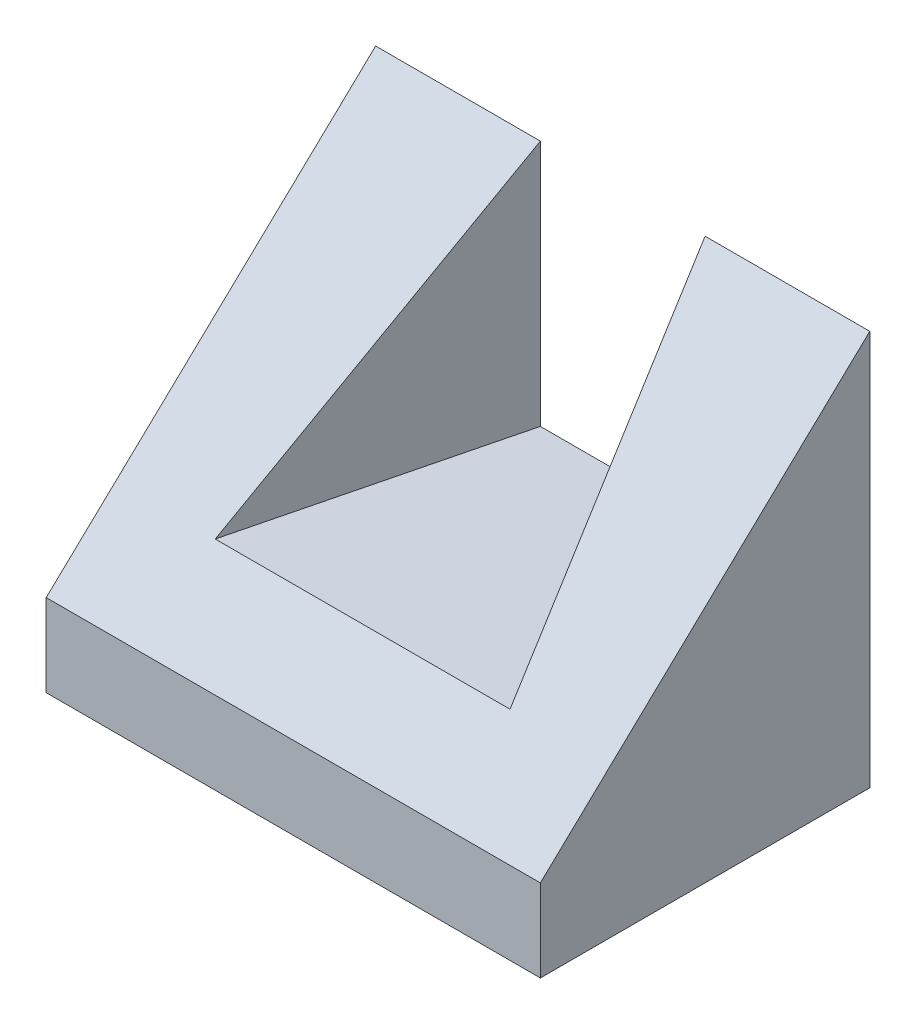
SolidWorks part; units mm, degrees
ref_plane "前基準面" through (0, 0, 0) normal (0, 0, 1) x (1, 0, 0)
ref_plane "上基準面" through (0, 0, 0) normal (0, 1, 0) x (1, 0, 0)
ref_plane "右基準面" through (0, 0, 0) normal (1, 0, 0) x (0, 0, -1)
sketch "草圖1" plane through (0, 0, 0) normal (0, 0, 1) x (1, 0, 0)
  line L1 (-15, 12) -> (15, 12)
  line L2 (-15, 12) -> (-15, -12)
  line L3 (-15, -12) -> (15, -12)
  line L4 (15, 12) -> (15, -12)
  line L5 (-15, 12) -> (15, -12) construction
  line L6 (-15, -12) -> (15, 12) construction
  point P0 (0, 0)
  dimension "D1" = 30
  dimension "D2" = 24
extrude "填料-伸長1" add sketch "草圖1" against normal blind 20
sketch "草圖2" plane through (0, 12, 0) normal (0, 1, 0) x (1, 0, 0)
  line L0 (5, 20) -> (10, 0)
  line L1 (15, 20) -> (-15, 20) construction
  line L2 (15, 0) -> (-15, 0) construction
  line L3 (10, 0) -> (-10, 0)
  line L4 (-10, 0) -> (-5, 20)
  line L5 (-5, 20) -> (5, 20)
  line L6 (5, 20) -> (5.0354, 19.9313)
  line L7 (0, 0) -> (0, 20) construction
  line M3 (-15, 0) -> (15, 0)
  line M5 (15, 20) -> (-15, 20)
  dimension "D1" = 10
  dimension "D2" = 20
extrude "除料-伸長1" cut sketch "草圖2" against normal blind 15 contours L7 L5 L4 M3 | L7 L3 L0 M5
sketch "草圖3" plane through (15, 0, 0) normal (1, 0, 0) x (0, 0, -1)
  line L0 (0, -7) -> (20, 12)
  line L1 (0, -12) -> (0, 12) construction
  line L2 (20, 12) -> (0, 12) construction
  line L3 (20, 12) -> (0, 12)
  line L4 (0, 12) -> (0, -7)
  line L5 (20, -12) -> (0, -12) construction
  dimension "D1" = 5
  dimension "D2" = 20
extrude "除料-伸長2" cut sketch "草圖3" against normal through all
